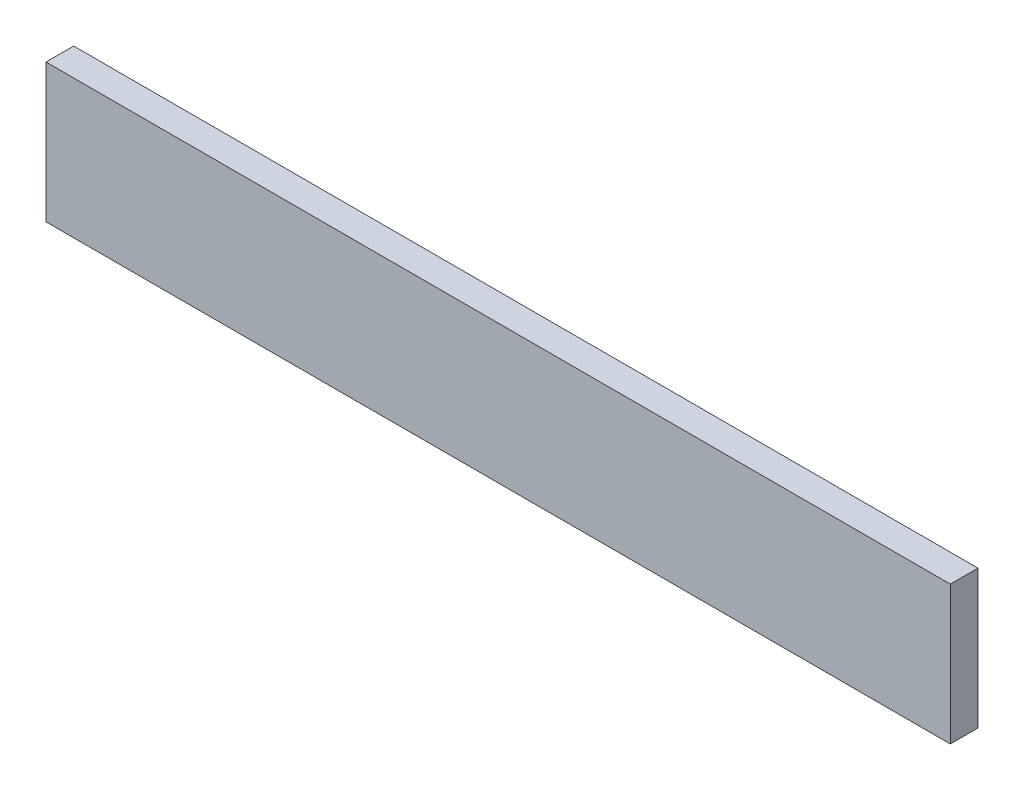
SolidWorks part; units mm, degrees
material "Pine"
ref_plane "Piano frontale" through (0, 0, 0) normal (0, 0, 1) x (1, 0, 0)
ref_plane "Piano superiore" through (0, 0, 0) normal (0, 1, 0) x (1, 0, 0)
ref_plane "Piano destro" through (0, 0, 0) normal (1, 0, 0) x (0, 0, -1)
sketch "Sketch1" plane through (0, 0, 0) normal (0, 0, 1) x (1, 0, 0)
  line L1 (0, 0) -> (49, 0)
  line L2 (0, 0) -> (0, 7.5)
  line L3 (0, 7.5) -> (49, 7.5)
  line L4 (49, 0) -> (49, 7.5)
  dimension "D1" = 49
  dimension "D2" = 7.5
extrude "Boss-Extrude1" add sketch "Sketch1" along normal blind 1.5
scale "Scale1" scale about origin uniform scaling yes scale factor 10
